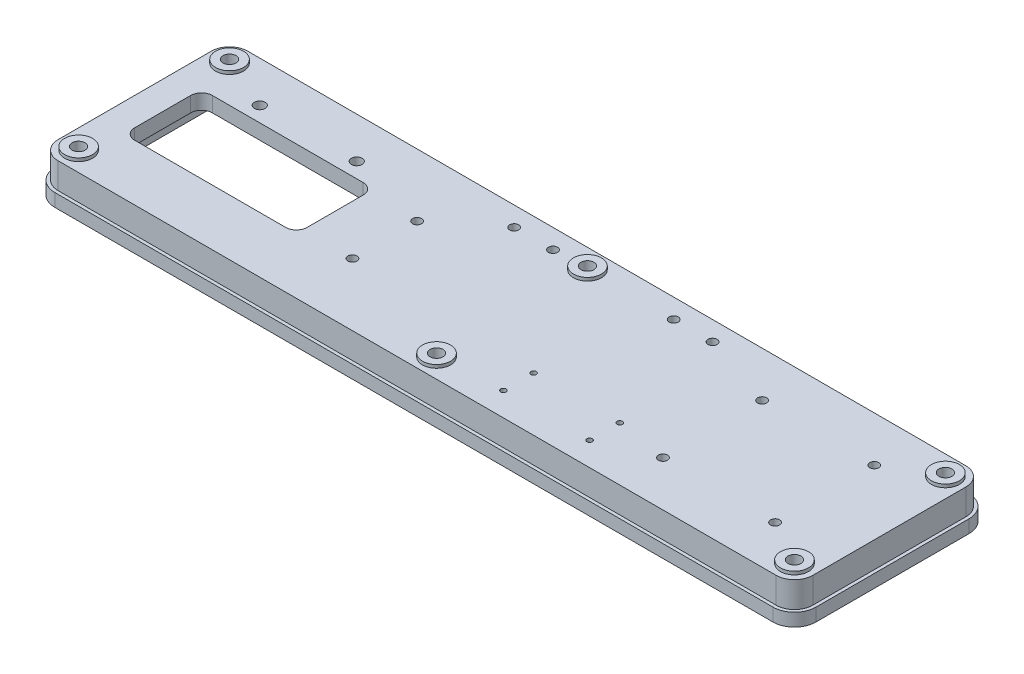
SolidWorks part; units mm, degrees
material "6061-T6 (SS)"
ref_plane "Front Plane" through (0, 0, 0) normal (0, 0, 1) x (1, 0, 0)
ref_plane "Top Plane" through (0, 0, 0) normal (0, 1, 0) x (1, 0, 0)
ref_plane "Right Plane" through (0, 0, 0) normal (1, 0, 0) x (0, 0, -1)
sketch "Sketch1" plane through (0, 0, 0) normal (0, 1, 0) x (1, 0, 0)
  line L1 (176.5, -45.5) -> (-176.5, -45.5)
  line L2 (176.5, -45.5) -> (176.5, 45.5)
  line L3 (176.5, 45.5) -> (-176.5, 45.5)
  line L4 (-176.5, -45.5) -> (-176.5, 45.5)
  line L5 (176.5, -45.5) -> (-176.5, 45.5) construction
  line L6 (176.5, 45.5) -> (-176.5, -45.5) construction
  point P0 (0, 0)
  dimension "D1" = 91
  dimension "D2" = 353
extrude "Boss-Extrude1" add sketch "Sketch1" along normal blind 18
fillet "Fillet1" radius 10 4 edges at (-176.5, 9, -45.5) (-176.5, 9, 45.5) (176.5, 9, -45.5) (176.5, 9, 45.5)
sketch "Sketch3" plane through (0, 18, 0) normal (0, 1, 0) x (1, 0, 0)
  line L24 (-175, 35.5) -> (-175, -35.5)
  line L25 (-166.5, -44) -> (166.5, -44)
  line L26 (175, -35.5) -> (175, 35.5)
  line L27 (166.5, 44) -> (-166.5, 44)
  line L28 (-175, 35.5) -> (-175, -35.5)
  line L29 (-166.5, -44) -> (166.5, -44)
  line L30 (175, -35.5) -> (175, 35.5)
  line L31 (166.5, 44) -> (-166.5, 44)
  arc A20 (-166.5, 44) -> (-175, 35.5) centre (-166.5, 35.5) ccw
  arc A21 (-175, -35.5) -> (-166.5, -44) centre (-166.5, -35.5) ccw
  arc A22 (166.5, -44) -> (175, -35.5) centre (166.5, -35.5) ccw
  arc A23 (175, 35.5) -> (166.5, 44) centre (166.5, 35.5) ccw
  arc A24 (-166.5, 44) -> (-175, 35.5) centre (-166.5, 35.5) ccw
  arc A25 (-175, -35.5) -> (-166.5, -44) centre (-166.5, -35.5) ccw
  arc A26 (166.5, -44) -> (175, -35.5) centre (166.5, -35.5) ccw
  arc A27 (175, 35.5) -> (166.5, 44) centre (166.5, 35.5) ccw
  dimension "D1" = 1.5
extrude "Cut-Extrude1" cut sketch "Sketch3" against normal blind 12 flip side to cut
sketch "Sketch4" plane through (0, 0, 0) normal (0, -1, 0) x (1, 0, 0)
  line L28 (-170, 35.5) -> (-170, -35.5)
  line L29 (166.5, 39) -> (-166.5, 39)
  line L30 (170, -35.5) -> (170, 35.5)
  line L31 (-166.5, -39) -> (166.5, -39)
  line L32 (-170, 35.5) -> (-170, -35.5)
  line L33 (166.5, 39) -> (-166.5, 39)
  line L34 (170, -35.5) -> (170, 35.5)
  line L35 (-166.5, -39) -> (166.5, -39)
  arc A22 (-170, -35.5) -> (-166.5, -39) centre (-166.5, -35.5) ccw
  arc A23 (-166.5, 39) -> (-170, 35.5) centre (-166.5, 35.5) ccw
  arc A24 (170, 35.5) -> (166.5, 39) centre (166.5, 35.5) ccw
  arc A25 (166.5, -39) -> (170, -35.5) centre (166.5, -35.5) ccw
  arc A26 (-170, -35.5) -> (-166.5, -39) centre (-166.5, -35.5) ccw
  arc A27 (-166.5, 39) -> (-170, 35.5) centre (-166.5, 35.5) ccw
  arc A28 (170, 35.5) -> (166.5, 39) centre (166.5, 35.5) ccw
  arc A29 (166.5, -39) -> (170, -35.5) centre (166.5, -35.5) ccw
  dimension "D1" = 5
extrude "Cut-Extrude2" cut sketch "Sketch4" against normal blind 11
sketch "Sketch5" plane through (0, 18, 0) normal (0, 1, 0) x (1, 0, 0)
  line L0 (-175, 35.5) -> (-175, -35.5) construction
  line L1 (175, -35.5) -> (175, 35.5) construction
  line L2 (166.5, 44) -> (-166.5, 44) construction
  line L3 (-175, 0) -> (175, 0) construction
  line L4 (-175, 35.5) -> (-175, -35.5) construction
  line L5 (0, 44) -> (0, -44) construction
  line L7 (166.5, 44) -> (-166.5, 44) construction
  line L8 (-166.5, -44) -> (166.5, -44) construction
  circle A0 centre (-166, 35) radius 6.5
  circle A1 centre (-166, -35) radius 6.5
  circle A2 centre (0, 35) radius 6.5
  circle A3 centre (0, -35) radius 6.5
  circle A4 centre (166, 35) radius 6.5
  circle A5 centre (166, -35) radius 6.5
  dimension "D1" = 13
  dimension "D2" = 9
  dimension "D3" = 9
  dimension "D5" = 166
  dimension "D4" = 3
extrude "Boss-Extrude2" add sketch "Sketch5" along normal blind 1.5
sketch "Sketch8" plane through (0, 18, 0) normal (0, 1, 0) x (1, 0, 0)
  line L0 (-175, 35.5) -> (-175, -35.5) construction
  line L1 (-82, -18) -> (-162, -18)
  line L2 (-82, -18) -> (-82, 18)
  line L3 (-82, 18) -> (-162, 18)
  line L4 (-162, -18) -> (-162, 18)
  line L5 (-82, -18) -> (-162, 18) construction
  line L6 (-82, 18) -> (-162, -18) construction
  point P0 (-122, 0)
  dimension "D1" = 36
  dimension "D2" = 80
  dimension "D3" = 13
extrude "Cut-Extrude3" cut sketch "Sketch8" against normal up to next
fillet "Fillet2" radius 5 4 edges at (-82, 14.5, -18) (-82, 14.5, 18) (-162, 14.5, 18) (-162, 14.5, -18)
hole_wizard "Ø6.0 (6) Diameter Hole1" positions "Sketch6" profile "Sketch7" hole size "Ø6.0" standard "ANSI Metric" end condition up to next
sketch "Sketch6" plane through (0, 19.5, 0) normal (0, 1, 0) x (1, 0, 0)
  point P0 (-166, -35)
  point P3 (-166, 35)
  point P6 (0, 35)
  point P9 (0, -35)
  point P12 (166, 35)
  point P15 (166, -35)
sketch "Sketch7" plane through (-166, 19.5, 35) normal (1, 0, 0) x (0, 0, 1)
  line L0 (0, 0) -> (0, 8.5)
  line L1 (0, 8.5) -> (3, 8.5)
  line L2 (3, 8.5) -> (3, 0)
  line L5 (3, 0) -> (0, 0)
  line L11 (0, -6.35) -> (0, 107.95) construction
  dimension "Thru Hole Dia." = 6
  dimension "Thru Hole Depth" = 8.5
hole_wizard "M5x0.8 Tapped Hole1" positions "Sketch9" profile "Sketch10" tap size "M5x0.8" standard "ANSI Metric" end condition up to next
sketch "Sketch9" plane through (0, 18, 0) normal (0, 1, 0) x (1, 0, 0)
  line L0 (175, 0) -> (-82, 0) construction
  line L1 (175, -35.5) -> (175, 35.5) construction
  line L2 (-82, -13) -> (-82, 13) construction
  line L4 (0, 45.5) -> (0, -44) construction
  line L5 (166.5, 45.5) -> (-166.5, 45.5) construction
  line L6 (-166.5, -44) -> (166.5, -44) construction
  line L8 (166.5, 44) -> (-166.5, 44) construction
  point P0 (-34, 35)
  point P2 (-16, 35)
  point P4 (40, 35)
  point P6 (58, 35)
  point P8 (-59, 15)
  point P10 (-59, -15)
  point P12 (93, -23)
  point P14 (145, -23)
  point P16 (145, 23)
  point P18 (93, 23)
  dimension "D1" = 15
  dimension "D2" = 9
  dimension "D3" = 16
  dimension "D4" = 18
  dimension "D5" = 40
  dimension "D6" = 18
  dimension "D7" = 30
  dimension "D8" = 52
  dimension "D9" = 46
  dimension "D10" = 152
sketch "Sketch10" plane through (-34, 18, -35) normal (1, 0, 0) x (0, 0, 1)
  line L0 (0, 0) -> (0, 7)
  line L1 (0, 7) -> (2.1, 7)
  line L2 (2.1, 7) -> (2.1, 0)
  line L5 (2.1, 0) -> (0, 0)
  line L11 (0, -6.35) -> (0, 107.95) construction
  dimension "Thru Tap Drill Dia." = 4.2
  dimension "Thru Tap Drill Depth" = 7
cosmetic thread "Hole Thread1" parameters "D2"=5
cosmetic thread "Hole Thread2" parameters "D2"=5
cosmetic thread "Hole Thread3" parameters "D2"=5
cosmetic thread "Hole Thread4" parameters "D2"=5
cosmetic thread "Hole Thread5" parameters "D2"=5
cosmetic thread "Hole Thread6" parameters "D2"=5
cosmetic thread "Hole Thread7" parameters "D2"=5
cosmetic thread "Hole Thread8" parameters "D2"=5
cosmetic thread "Hole Thread9" parameters "D2"=5
cosmetic thread "Hole Thread10" parameters "D2"=5
hole_wizard "M6x1.0 Tapped Hole1" positions "Sketch11" profile "Sketch12" tap size "M6x1.0" standard "ANSI Metric" end condition up to next
sketch "Sketch11" plane through (0, 18, 0) normal (0, 1, 0) x (1, 0, 0)
  line L0 (-175, 35.5) -> (-175, -35.5) construction
  line L1 (-166, 35) -> (166, 35) construction
  line L2 (166, 35) -> (166, -35) construction
  line L3 (166, -35) -> (-166, -35) construction
  line L4 (-166, -35) -> (-166, 35) construction
  point P0 (-142, 25)
  point P2 (-97, 25)
  dimension "D1" = 33
  dimension "D2" = 45
  dimension "D3" = 10
sketch "Sketch12" plane through (-142, 18, -25) normal (1, 0, 0) x (0, 0, 1)
  line L0 (0, 0) -> (0, 7)
  line L1 (0, 7) -> (2.5, 7)
  line L2 (2.5, 7) -> (2.5, 0)
  line L5 (2.5, 0) -> (0, 0)
  line L11 (0, -6.35) -> (0, 107.95) construction
  dimension "Thru Tap Drill Dia." = 5
  dimension "Thru Tap Drill Depth" = 7
cosmetic thread "Hole Thread11" parameters "D2"=6
cosmetic thread "Hole Thread12" parameters "D2"=6
hole_wizard "M3x0.5 Tapped Hole1" positions "Sketch13" profile "Sketch14" tap size "M3x0.5" standard "ANSI Metric" end condition up to next
sketch "Sketch13" plane through (0, 18, 0) normal (0, 1, 0) x (1, 0, 0)
  line L0 (-166.5, -44) -> (166.5, -44) construction
  point P0 (29, -33)
  point P2 (69, -33)
  point P4 (69, -19)
  point P6 (29, -19)
  dimension "D1" = 40
  dimension "D2" = 14
  dimension "D3" = 11
  dimension "D4" = 29
sketch "Sketch14" plane through (29, 18, 33) normal (1, 0, 0) x (0, 0, 1)
  line L0 (0, 0) -> (0, 7)
  line L1 (0, 7) -> (1.25, 7)
  line L2 (1.25, 7) -> (1.25, 0)
  line L5 (1.25, 0) -> (0, 0)
  line L11 (0, -6.35) -> (0, 107.95) construction
  dimension "Thru Tap Drill Dia." = 2.5
  dimension "Thru Tap Drill Depth" = 7
cosmetic thread "Hole Thread13" parameters "D2"=3
cosmetic thread "Hole Thread14" parameters "D2"=3
cosmetic thread "Hole Thread15" parameters "D2"=3
cosmetic thread "Hole Thread16" parameters "D2"=3
